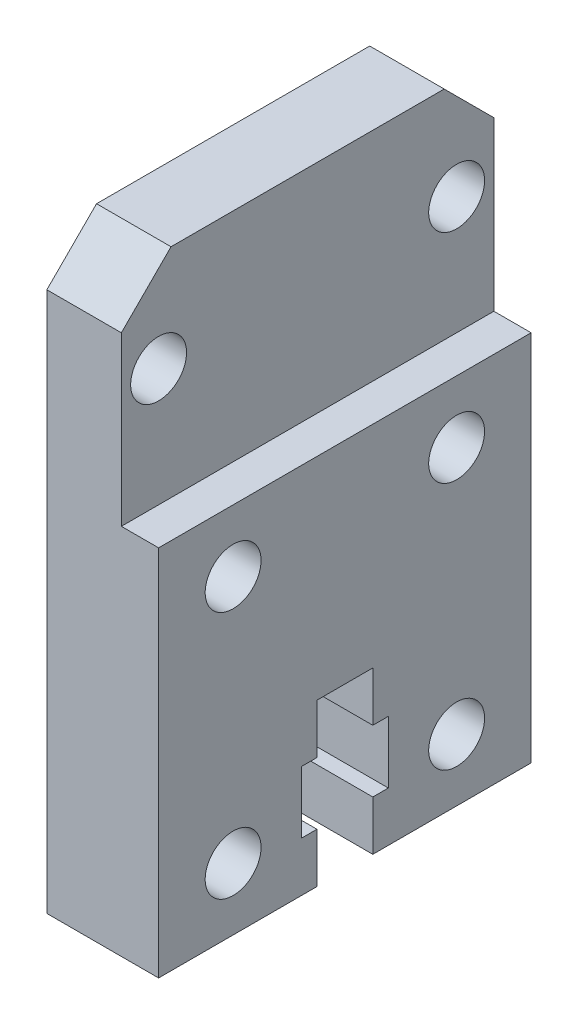
SolidWorks part; units mm, degrees
material "Printed PLA"
ref_plane "Front Plane" through (0, 0, 0) normal (0, 0, 1) x (1, 0, 0)
ref_plane "Top Plane" through (0, 0, 0) normal (0, 1, 0) x (1, 0, 0)
ref_plane "Right Plane" through (0, 0, 0) normal (1, 0, 0) x (0, 0, -1)
sketch "Sketch1" plane through (0, 0, 0) normal (1, 0, 0) x (0, 0, -1)
  line L0 (0, 0) -> (0, 8) construction
  line L1 (-15, 8) -> (15, 8)
  line L2 (-15, 8) -> (-15, -39.5)
  line L3 (-15, -39.5) -> (15, -39.5)
  line L4 (15, 8) -> (15, -39.5)
  circle A0 centre (0, 0) radius 6.5 construction
  dimension "D1" = 13
  dimension "D2" = 8
  dimension "D3" = 30
  dimension "D4" = 47.5
extrude "Boss-Extrude1" add sketch "Sketch1" along normal blind 6
sketch "Sketch2" plane through (0, 0, 15) normal (0, 0, 1) x (1, 0, 0)
  line L0 (6, -39.5) -> (16.5, -39.5)
  line L1 (16.5, -39.5) -> (16.5, -32)
  line L2 (9, -24.5) -> (9, -9.5)
  line L3 (9, -9.5) -> (6, -9.5)
  line L4 (6, 8) -> (6, -39.5) construction
  line L5 (6, -9.5) -> (6, -39.5)
  arc A0 (16.5, -32) -> (9, -24.5) centre (16.5, -24.5) cw
  dimension "D1" = 7.5
  dimension "D2" = 3
  dimension "D3" = 15
  dimension "D4" = 30
extrude "Boss-Extrude2" add sketch "Sketch2" against normal up to surface (30 mm away) up to face at (3, -15.75, -15)
sketch "Sketch3" plane through (0, 0, 15) normal (0, 0, 1) x (1, 0, 0)
  line L0 (16.5, -29.5) -> (16.5, -32)
  line L1 (9, -24.5) -> (9, -9.5) construction
  line L2 (9, -24.5) -> (11.5, -24.5)
  arc A0 (11.5, -24.5) -> (16.5, -29.5) centre (16.5, -24.5) ccw
  arc A1 (16.5, -32) -> (9, -24.5) centre (16.5, -24.5) cw
  arc A2 (9, -24.5) -> (16.5, -32) centre (16.5, -24.5) ccw construction
  dimension "D1" = 10
extrude "Boss-Extrude3" add sketch "Sketch3" against normal offset from surface (3 mm away) 12 up to plane "Front Plane"
mirror "Mirror1" about plane through (0, 0, 0) normal (0, 0, 1) of "Boss-Extrude3"
sketch "Sketch4" plane through (16.5, 0, 0) normal (1, 0, 0) x (0, 0, -1)
  line L0 (-15, -39.5) -> (-15, -29.5) construction
  line L1 (-12, -32) -> (12, -32)
  line L2 (-15, -29.5) -> (-15, -39.5)
  line L3 (-15, -39.5) -> (15, -39.5)
  line L4 (15, -29.5) -> (15, -39.5)
  line L5 (12, -32) -> (-12, -32) construction
  line L7 (-15, -29.5) -> (-12, -29.5)
  line L10 (-12, -29.5) -> (-12, -32)
  line L11 (15, -29.5) -> (12, -29.5)
  line L14 (12, -29.5) -> (12, -32)
extrude "Boss-Extrude4" add sketch "Sketch4" along normal blind 12.5
sketch "Sketch5" plane through (6, 0, 0) normal (1, 0, 0) x (0, 0, -1)
  line L0 (12, 0) -> (-12, 0) construction
  line L1 (0, 0) -> (0, 8) construction
  line L2 (15, 8) -> (-15, 8) construction
  circle A0 centre (-12, 0) radius 2.25
  circle A1 centre (12, 0) radius 2.25
  dimension "D1" = 4.5
  dimension "D2" = 0
  dimension "D3" = 24
extrude "Cut-Extrude1" cut sketch "Sketch5" against normal through all
sketch "Sketch8" plane through (0, 0, 15) normal (0, 0, 1) x (1, 0, 0)
  line L1 (9, -24.5) -> (29, -24.5)
  line L2 (9, -24.5) -> (9, -39.5)
  line L3 (9, -39.5) -> (29, -39.5)
  line L4 (29, -24.5) -> (29, -39.5)
extrude "Cut-Extrude4" cut sketch "Sketch8" against normal through all
sketch "Sketch9" plane through (9, 0, 0) normal (1, 0, 0) x (0, 0, -1)
  line L0 (-9, -34.5) -> (-9, -14.5) construction
  line L1 (-9, -14.5) -> (9, -14.5) construction
  line L2 (9, -14.5) -> (9, -34.5) construction
  line L3 (9, -34.5) -> (-9, -34.5) construction
  line L4 (-9, -34.5) -> (9, -14.5) construction
  line L5 (0, -24.5) -> (0, 0) construction
  line L6 (15, -39.5) -> (-15, -39.5) construction
  circle A0 centre (-9, -14.5) radius 2.25
  circle A1 centre (9, -14.5) radius 2.25
  circle A2 centre (9, -34.5) radius 2.25
  circle A3 centre (-9, -34.5) radius 2.25
  dimension "D4" = 4.5
  dimension "D1" = 18
  dimension "D2" = 20
  dimension "D3" = 15
extrude "Cut-Extrude5" cut sketch "Sketch9" against normal through all
sketch "Sketch10" plane through (0, 0, 0) normal (-1, 0, 0) x (0, 0, 1)
  line L1 (-13.0415, -14.5) -> (-11.0207, -18)
  line L2 (-11.0207, -18) -> (-6.9793, -18)
  line L3 (-6.9793, -18) -> (-4.9585, -14.5)
  line L4 (-4.9585, -14.5) -> (-6.9793, -11)
  line L5 (-6.9793, -11) -> (-11.0207, -11)
  line L6 (-11.0207, -11) -> (-13.0415, -14.5)
  line L7 (4.9585, -14.5) -> (6.9793, -18)
  line L8 (6.9793, -18) -> (11.0207, -18)
  line L9 (11.0207, -18) -> (13.0415, -14.5)
  line L10 (13.0415, -14.5) -> (11.0207, -11)
  line L11 (11.0207, -11) -> (6.9793, -11)
  line L12 (6.9793, -11) -> (4.9585, -14.5)
  line L13 (4.9585, -34.5) -> (6.9793, -38)
  line L14 (6.9793, -38) -> (11.0207, -38)
  line L15 (11.0207, -38) -> (13.0415, -34.5)
  line L16 (13.0415, -34.5) -> (11.0207, -31)
  line L17 (11.0207, -31) -> (6.9793, -31)
  line L18 (6.9793, -31) -> (4.9585, -34.5)
  line L19 (-13.0415, -34.5) -> (-11.0207, -38)
  line L20 (-11.0207, -38) -> (-6.9793, -38)
  line L21 (-6.9793, -38) -> (-4.9585, -34.5)
  line L22 (-4.9585, -34.5) -> (-6.9793, -31)
  line L23 (-6.9793, -31) -> (-11.0207, -31)
  line L24 (-11.0207, -31) -> (-13.0415, -34.5)
  circle A0 centre (-9, -14.5) radius 3.5 construction
  circle A1 centre (9, -14.5) radius 3.5 construction
  circle A2 centre (9, -34.5) radius 3.5 construction
  circle A3 centre (-9, -34.5) radius 3.5 construction
  dimension "D1" = 7
extrude "Cut-Extrude6" cut sketch "Sketch10" against normal blind 5
chamfer "Chamfer1" distance 4 angle 45 2 edges at (3, 8, -15) (3, 8, 15)
sketch "Sketch12" plane through (9, 0, 0) normal (1, 0, 0) x (0, 0, -1)
  line L0 (15, -39.5) -> (-15, -39.5) construction
  line L1 (-2.25, -39.5) -> (2.25, -39.5)
  line L2 (-2.25, -39.5) -> (-2.25, -35.5)
  line L3 (-2.25, -26.5) -> (2.25, -26.5)
  line L4 (2.25, -39.5) -> (2.25, -35.5)
  line L5 (2.25, -30.5) -> (2.25, -26.5)
  line L6 (-3.5, -30.5) -> (-2.25, -30.5)
  line L7 (-3.5, -30.5) -> (-3.5, -35.5)
  line L8 (-3.5, -35.5) -> (-2.25, -35.5)
  line L9 (3.5, -30.5) -> (3.5, -35.5)
  line L10 (-2.25, -30.5) -> (-2.25, -26.5)
  line L11 (2.25, -30.5) -> (3.5, -30.5)
  line L12 (2.25, -35.5) -> (3.5, -35.5)
  line L13 (0, -26.5) -> (0, 0) construction
  dimension "D1" = 4.5
  dimension "D2" = 5
  dimension "D3" = 7
  dimension "D4" = 4
  dimension "D5" = 4
extrude "Cut-Extrude7" cut sketch "Sketch12" against normal through all
